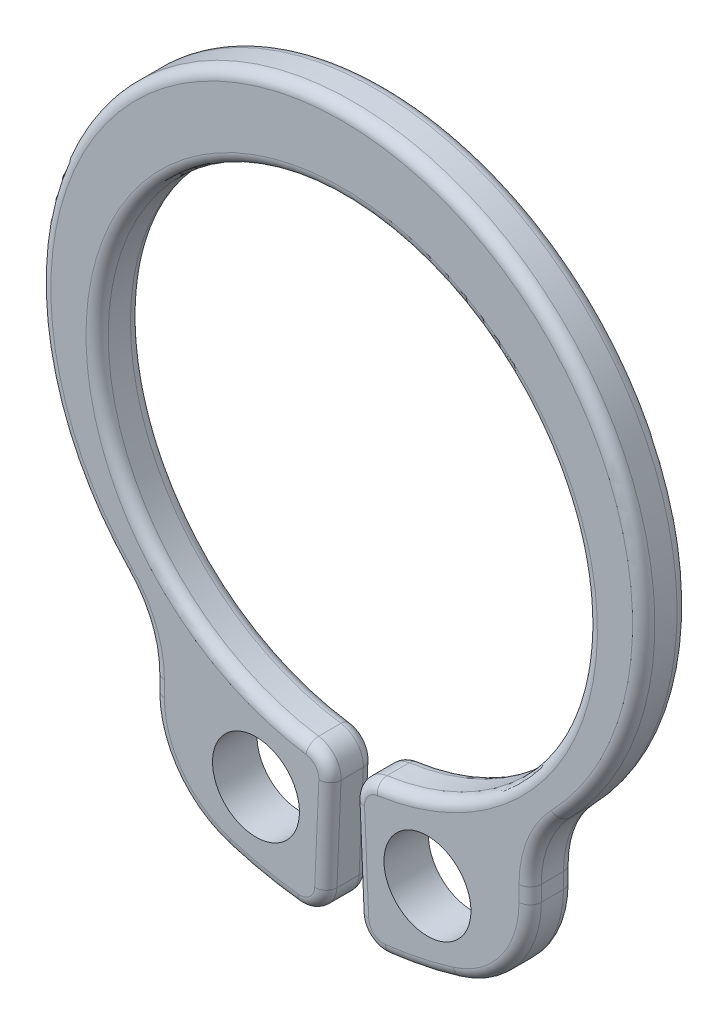
SolidWorks part; units mm, degrees
ref_plane "Front" through (0, 0, 0) normal (0, 0, 1) x (1, 0, 0)
ref_plane "Top" through (0, 0, 0) normal (0, 1, 0) x (1, 0, 0)
ref_plane "Right" through (0, 0, 0) normal (1, 0, 0) x (0, 0, -1)
sketch "Sketch1" plane through (0, 0, 0) normal (0, 0, 1) x (1, 0, 0)
  line L0 (0, 0) -> (-4.7631, -2.75) construction
  line L1 (0, 8.8) -> (0, -8.8) construction
  line L2 (-4.2384, -7.7216) -> (-4.2356, -4.7979) construction
  line L3 (0, 0) -> (4.7631, -2.75) construction
  line L4 (-4.2356, -4.7979) -> (-4.8312, -5.4726) construction
  line L5 (-4.2356, -4.7979) -> (0, 0) construction
  line L6 (0, 5.5) -> (0, 7.3) construction
  line L7 (0, 7.3) -> (0, 6.4) construction
  line L8 (0, -5.5) -> (0, -8.8) construction
  line L9 (-2.3734, -8.4826) -> (0, 0) construction
  line L10 (0, 0) -> (-0.3842, -8.8) construction
  line L11 (-4.2384, -7.7216) -> (0, 0) construction
  line L12 (-4.2365, -5.6809) -> (-4.8885, -4.2034) construction
  line L13 (-4.5625, -4.9421) -> (-4.2356, -4.7979) construction
  line L14 (-1.482, -5.2966) -> (-2.3734, -8.4826) construction
  line L15 (-1.9277, -6.8896) -> (-1.1091, -7.1186) construction
  arc A0 (0, 7.3) -> (-4.2356, -4.7979) centre (0, 0.5096) ccw construction
  circle A2 centre (0, 0) radius 7.3 construction
  arc A3 (-4.2384, -7.7216) -> (-0.3842, -8.8) centre (0, 0) ccw construction
  circle A4 centre (0, 0) radius 5.5 construction
  circle A6 centre (-1.9277, -6.8896) radius 0.85 construction
  arc A7 (-4.8885, -4.2034) -> (-4.2365, -5.6809) centre (-6.5769, -5.8311) cw construction
  point P5 (-4.7631, -2.75)
  point P11 (4.7631, -2.75)
  point P24 (-3.5126, -6.3993)
  point P35 (0, 7.3)
  point P36 (0, 5.5)
  point P37 (0, -5.5)
  point P38 (0, -8.8)
  dimension "Ring ID" = 11
  dimension "Hole Diameter" = 1.7
  dimension "D10" = 2.3452
  dimension "Max Sec." = 1.8
  dimension "Lug Height" = 3.3
  dimension "D6" = 2.5
  dimension "D5" = 2.9237
  dimension "D8" = 1.615
  dimension "D3" = 120
  dimension "D7" = 60
  dimension "D2" = 4.0375
  dimension "D4" = 1.615
sketch "Sketch5" plane through (0, 0, 0) normal (0, 1, 0) x (1, 0, 0)
  line L0 (-7.3, 0.5) -> (-7.3, -0.5) construction
  line L2 (0, 0.5) -> (0, -0.5) construction
  line L4 (-7.3, 0) -> (7.3, 0) construction
  point P3 (-7.3, 0)
  point P6 (0, 0)
  dimension "Ring Thickness" = 1
sketch "Sketch2" plane through (0, 0, 0) normal (0, 0, 1) x (1, 0, 0)
  line L0 (-4.2384, -7.7216) -> (-4.2356, -4.7979) construction
  line L1 (-4.2384, -7.7216) -> (-4.2356, -4.7979)
  line L2 (0, 7.3) -> (0, 5.5)
  line L3 (-0.3842, -8.8) -> (-0.2399, -5.4948)
  line L4 (0, 0) -> (-0.3842, -8.8) construction
  arc A0 (0, 7.3) -> (-4.2356, -4.7979) centre (0, 0.5096) ccw construction
  arc A1 (-4.2384, -7.7216) -> (-0.3842, -8.8) centre (0, 0) ccw construction
  circle A2 centre (-1.9277, -6.8896) radius 0.85 construction
  circle A3 centre (-1.9277, -6.8896) radius 0.9775
  arc A4 (0, 7.3) -> (-4.2356, -4.7979) centre (0, 0.5096) ccw
  arc A5 (-4.2384, -7.7216) -> (-0.3842, -8.8) centre (0, 0) ccw
  circle A6 centre (-1.9277, -6.8896) radius 0.85 construction
  circle A7 centre (0, 0) radius 5.5 construction
  arc A8 (0, 5.5) -> (-0.2399, -5.4948) centre (0, 0) ccw
  dimension "D1" = 1.955
extrude "Boss-Extrude1" add sketch "Sketch2" along normal mid plane 1
fillet "Fillet1" radius 2.3452 2 edges at (-4.2356, -4.7979, 0) (-4.2384, -7.7216, 0)
fillet "Fillet2" radius 0.5863 2 edges at (-0.3842, -8.8, 0) (-0.2399, -5.4948, 0)
mirror "Mirror1" about plane through (0, 7.3, 0.5) normal (-1, 0, 0) of bodies 109
fillet "Fillet3" radius 0.25 32 edges at (-0.3991, -5.6519, -0.5) (-0.311, -7.1228, -0.5) (-0.563, -8.6139, -0.5) (-1.8019, -8.6221, -0.5) (-3.7779, -7.5739, -0.5) (-4.2368, -6.003, -0.5) (-4.4062, -4.9502, -0.5) (0, 7.3, -0.5) (4.4062, -4.9502, 0.5) (4.4062, -4.9502, -0.5) (4.2368, -6.003, -0.5) (4.2368, -6.003, 0.5) (3.7779, -7.5739, 0.5) (3.7779, -7.5739, -0.5) (1.8019, -8.6221, -0.5) (1.8019, -8.6221, 0.5) (0.563, -8.6139, 0.5) (0.563, -8.6139, -0.5) (0.311, -7.1228, 0.5) (0.311, -7.1228, -0.5) (0.3991, -5.6519, 0.5) (0.3991, -5.6519, -0.5) (-0.3991, -5.6519, 0.5) (-0.311, -7.1228, 0.5) (-0.563, -8.6139, 0.5) (-1.8019, -8.6221, 0.5) (-3.7779, -7.5739, 0.5) (-4.2368, -6.003, 0.5) (-4.4062, -4.9502, 0.5) (0, 7.3, 0.5) (0, 5.5, -0.5) (0, 5.5, 0.5)
sketch "Sketch3" plane through (0, 0, 0.5) normal (0, 0, 1) x (1, 0, 0)
  line L0 (4.2083, -3.5412) -> (4.8922, -4.1995) construction
  line L1 (4.8922, -4.1995) -> (5.5505, -3.5156) construction
  line L2 (0, 7.3) -> (0, 5.5) construction
  circle A0 centre (0, 0) radius 5.5 construction
  arc A1 (-4.8922, -4.1995) -> (4.8922, -4.1995) centre (0, 0.5096) ccw construction
equation "\"Thickness@Boss-Extrude1\"=\"Ring Thickness@Sketch5\""
equation "\"D2@Sketch1\"=\"Hole Diameter@Sketch1\"*2.375"
equation "\"D4@Sketch1\"=\"D2@Sketch1\"/2.5"
equation "\"D8@Sketch1\"=\"D4@Sketch1\""
equation "\"D1@Sketch2\"=\"Hole Diameter@Sketch1\"*1.15"
equation "\"D1@Fillet2\"=\"D10@Sketch1\" / 4"
equation "\"D1@Fillet3\"=\"Ring Thickness@Sketch5\"/4"
equation "\"D1@Fillet1\"=\"D10@Sketch1\""
